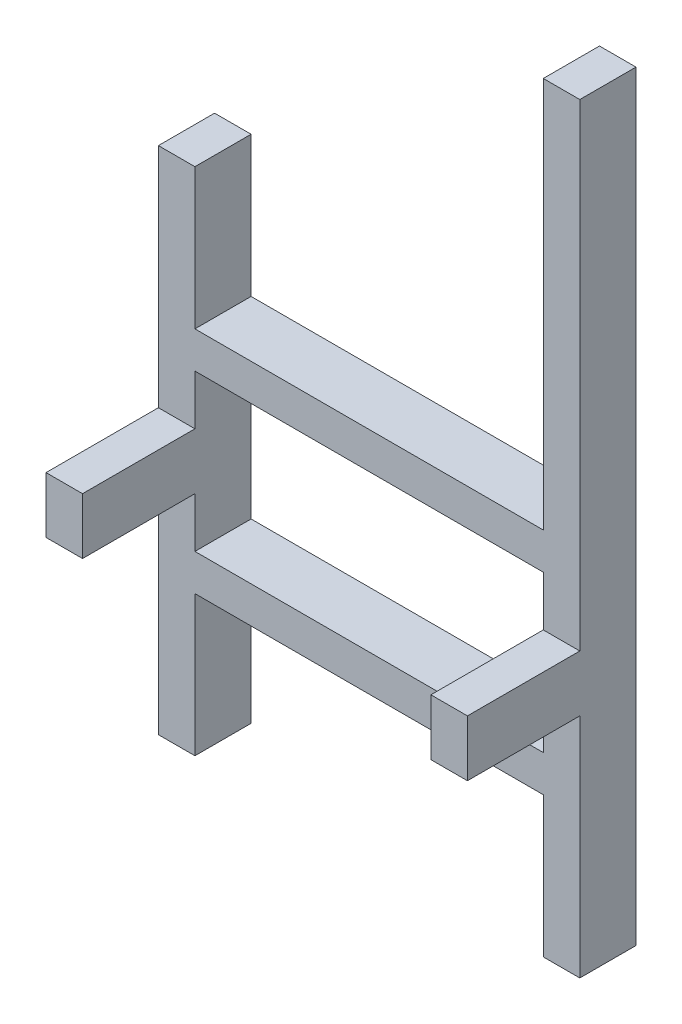
SolidWorks part; units mm, degrees
ref_plane "Front Plane" through (0, 0, 0) normal (0, 0, 1) x (1, 0, 0)
ref_plane "Top Plane" through (0, 0, 0) normal (0, 1, 0) x (1, 0, 0)
ref_plane "Right Plane" through (0, 0, 0) normal (1, 0, 0) x (0, 0, -1)
sketch "Sketch1" plane through (0, 0, 0) normal (0, 0, 1) x (1, 0, 0)
  line L0 (6.5, 0) -> (6.5, 25) construction
  line L1 (0, 90.8) -> (6.5, 90.8)
  line L2 (0, 90.8) -> (0, 0)
  line L3 (0, 0) -> (6.5, 0)
  line L4 (6.5, 90.8) -> (6.5, 0)
  line L5 (68.5, 135.4) -> (75, 135.4)
  line L6 (68.5, 135.4) -> (68.5, 0)
  line L7 (68.5, 0) -> (75, 0)
  line L8 (75, 135.4) -> (75, 0)
  line L9 (6.5, 0) -> (68.5, 0) construction
  line L10 (6.5, 25) -> (68.5, 25)
  line L11 (6.5, 25) -> (6.5, 31.5)
  line L12 (6.5, 31.5) -> (68.5, 31.5)
  line L13 (68.5, 25) -> (68.5, 31.5)
  line L14 (6.5, 90.8) -> (6.5, 65.8) construction
  line L16 (6.5, 65.8) -> (68.5, 65.8)
  line L17 (6.5, 65.8) -> (6.5, 59.3)
  line L18 (6.5, 59.3) -> (68.5, 59.3)
  line L19 (68.5, 65.8) -> (68.5, 59.3)
  point P15 (0, 0)
  point P16 (0, 0)
  dimension "D1" = 135.4
  dimension "D2" = 90.8
  dimension "D3" = 6.5
  dimension "D4" = 6.5
  dimension "D5" = 25
  dimension "D6" = 6.5
  dimension "D7" = 25
  dimension "D8" = 6.5
  dimension "D9" = 62
extrude "Boss-Extrude1" add sketch "Sketch1" along normal blind 10 contours L17 L16 L19 L18 | L2 L1 L4 L3 | L11 L10 L13 L12 | L6 L5 L8 L7
sketch "Sketch2" plane through (0, 0, 10) normal (0, 0, 1) x (1, 0, 0)
  line L0 (6.5, 59.3) -> (6.5, 31.5) construction
  line L1 (68.5, 59.3) -> (68.5, 31.5) construction
  line L2 (68.5, 45.4) -> (75, 45.4) construction
  line L3 (75, 135.4) -> (75, 0) construction
  line L4 (6.5, 45.4) -> (0, 45.4) construction
  line L5 (0, 90.8) -> (0, 0) construction
  line L7 (0, 40.4) -> (6.5, 40.4)
  line L8 (0, 40.4) -> (0, 50.4)
  line L9 (0, 50.4) -> (6.5, 50.4)
  line L10 (6.5, 40.4) -> (6.5, 50.4)
  line L11 (0, 40.4) -> (6.5, 50.4) construction
  line L12 (0, 50.4) -> (6.5, 40.4) construction
  line L13 (68.5, 40.4) -> (75, 40.4)
  line L14 (68.5, 40.4) -> (68.5, 50.4)
  line L15 (68.5, 50.4) -> (75, 50.4)
  line L16 (75, 40.4) -> (75, 50.4)
  line L17 (68.5, 40.4) -> (75, 50.4) construction
  line L18 (68.5, 50.4) -> (75, 40.4) construction
  point P16 (3.25, 45.4)
  point P21 (71.75, 45.4)
  dimension "D1" = 10
  dimension "D2" = 10
extrude "Boss-Extrude2" add sketch "Sketch2" along normal blind 20
